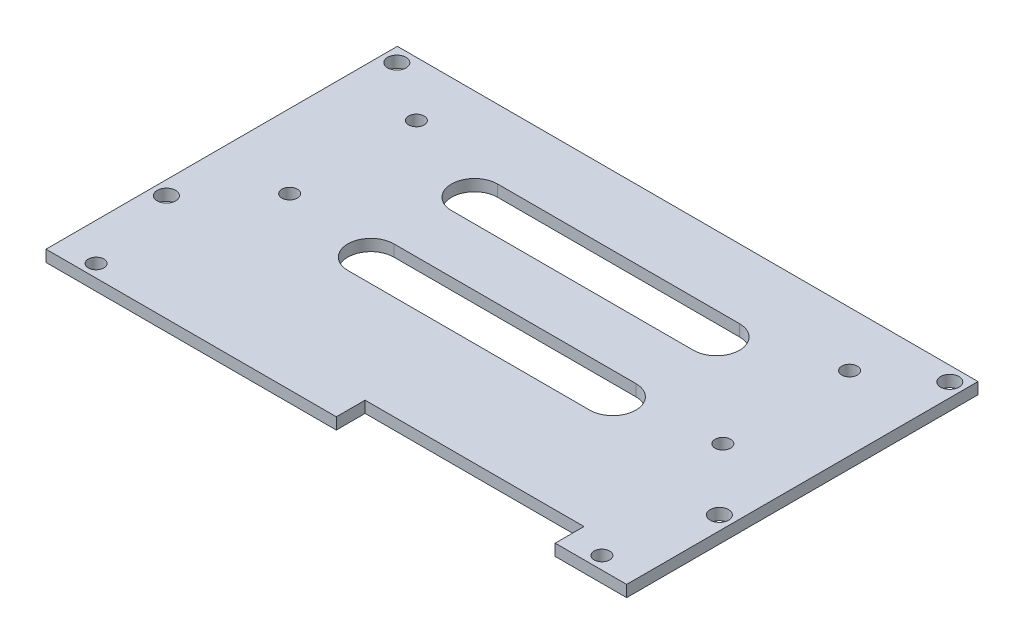
SolidWorks part; units mm, degrees
ref_plane "前视基准面" through (0, 0, 0) normal (0, 0, 1) x (1, 0, 0)
ref_plane "上视基准面" through (0, 0, 0) normal (0, 1, 0) x (1, 0, 0)
ref_plane "右视基准面" through (0, 0, 0) normal (1, 0, 0) x (0, 0, -1)
sketch "草图1" plane through (0, 0, 0) normal (0, 1, 0) x (1, 0, 0)
  line L0 (0, 27) -> (0, -27) construction
  line L1 (-40.4, 27) -> (40.4, 27) construction
  line L2 (-40.4, 27) -> (-40.4, -27) construction
  line L3 (-40.4, -27) -> (40.4, -27)
  line L4 (40.4, 27) -> (40.4, -27) construction
  line L5 (-40.4, 27) -> (40.4, -27) construction
  line L6 (-40.4, -27) -> (40.4, 27) construction
  line L7 (-21, 22) -> (21, 22)
  line L8 (-21, 4) -> (21, 4)
  line L9 (-21, 4) -> (-21, -4) construction
  line L10 (-21, -4) -> (21, -4)
  line L11 (21, 4) -> (21, -4) construction
  line L12 (-21, 4) -> (21, -4) construction
  line L13 (-21, -4) -> (21, 4) construction
  line L14 (-21, 14) -> (21, 14)
  line L17 (-40.4, 27) -> (-50.4, 27) construction
  line L18 (-50.4, 27) -> (-50.4, -27)
  line L19 (-50.4, -27) -> (-40.4, -27)
  line L20 (50.4, -27) -> (40.4, -27)
  line L21 (50.4, 27) -> (50.4, -27)
  line L22 (40.4, 27) -> (50.4, 27) construction
  line L23 (-29.4046, 0) -> (36.7711, 0) construction
  line L24 (-50.4, 27) -> (-50.4, 34)
  line L25 (-50.4, 34) -> (50.4, 34)
  line L26 (50.4, 34) -> (50.4, 27)
  arc A6 (-21, 4) -> (-21, -4) centre (-21, 0) ccw
  arc A7 (21, 4) -> (21, -4) centre (21, 0) cw
  arc A8 (-21, 22) -> (-21, 14) centre (-21, 18) ccw
  arc A9 (21, 22) -> (21, 14) centre (21, 18) cw
  circle A15 centre (-48, 31.5) radius 1.6
  circle A24 centre (-37.6, 24.5) radius 1.35
  circle A25 centre (-43.9, -24.8) radius 1.35
  circle A26 centre (37.6, 24.5) radius 1.35
  circle A27 centre (43.9, -24.8) radius 1.35
  circle A28 centre (-48, -8.5) radius 1.6
  circle A29 centre (48, -8.5) radius 1.6
  circle A30 centre (48, 31.5) radius 1.6
  circle A31 centre (-37.6, 2.5) radius 1.35
  circle A32 centre (37.6, 2.5) radius 1.35
  point P0 (0, 0)
  point P20 (0, 0)
  dimension "D3" = 3.2
  dimension "D12" = 2.7
  dimension "D6" = 37.6
  dimension "D13" = 2.7
  dimension "D1" = 80.8
  dimension "D2" = 54
  dimension "D4" = 48
  dimension "D5" = 2.5
  dimension "D7" = 8
  dimension "D8" = 42
  dimension "D11" = 10
  dimension "D14" = 49.3
  dimension "D10" = 24.5
  dimension "D15" = 6.3
  dimension "D16" = 7
  dimension "D17" = 40
  dimension "D18" = 22
  dimension "D9" = 2
extrude "凸台-拉伸1" add sketch "草图1" along normal blind 2
sketch "草图2" plane through (0, 0, 0) normal (0, -1, 0) x (1, 0, 0)
  line L0 (-50.4, 27) -> (50.4, 27) construction
  line L1 (0, 34.0093) -> (38, 34.0093)
  line L2 (0, 34.0093) -> (0, 22)
  line L3 (0, 22) -> (38, 22)
  line L4 (38, 34.0093) -> (38, 22)
  dimension "D1" = 38
  dimension "D2" = 5
extrude "切除-拉伸1" cut sketch "草图2" against normal up to next
